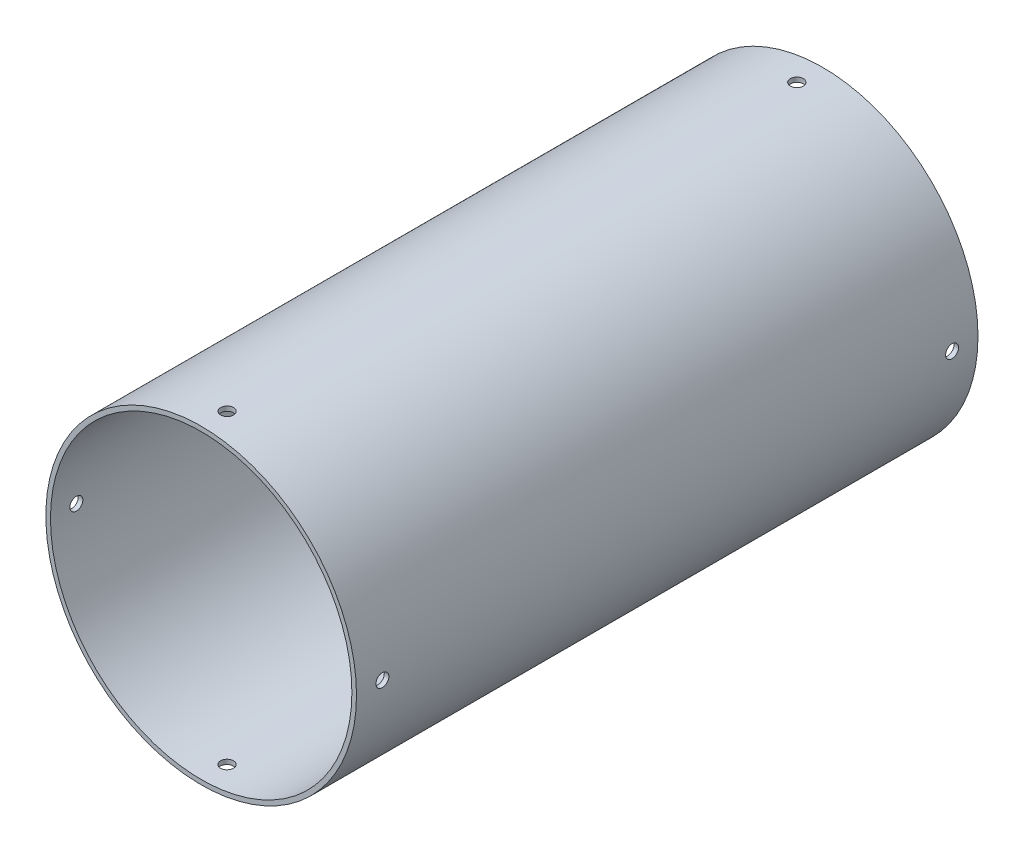
SolidWorks part; units mm, degrees
ref_plane "Front Plane" through (0, 0, 0) normal (0, 0, 1) x (1, 0, 0)
ref_plane "Top Plane" through (0, 0, 0) normal (0, 1, 0) x (1, 0, 0)
ref_plane "Right Plane" through (0, 0, 0) normal (1, 0, 0) x (0, 0, -1)
sketch "Sketch1" plane through (0, 0, 0) normal (0, 0, 1) x (1, 0, 0)
  circle A0 centre (0, 0) radius 76.1746
  circle A1 centre (0, 0) radius 73.914
  dimension "D1" = 152.3492
  dimension "D2" = 147.828
extrude "Boss-Extrude1" add sketch "Sketch1" along normal blind 304.8
ref_plane "Plane1" through (76.2, 0, 0) normal (1, 0, 0) x (0, 0, -1)
sketch "Sketch2" plane through (76.2, 0, 0) normal (1, 0, 0) x (0, 0, -1)
  line L0 (-304.8, 76.1746) -> (-304.8, -76.1746) construction
  line L1 (0, -76.1746) -> (0, 76.1746) construction
  circle A0 centre (-292.1, 0) radius 3.175
  circle A1 centre (-12.7, 0) radius 3.175
  dimension "D1" = 6.35
  dimension "D2" = 6.35
  dimension "D3" = 12.7
  dimension "D4" = 12.7
extrude "Cut-Extrude1" cut sketch "Sketch2" against normal blind 25.4
pattern_circular "CirPattern1" count 4 over 360 about axis through (0, 0, 304.8) along (0, 0, -1) of "Cut-Extrude1"
